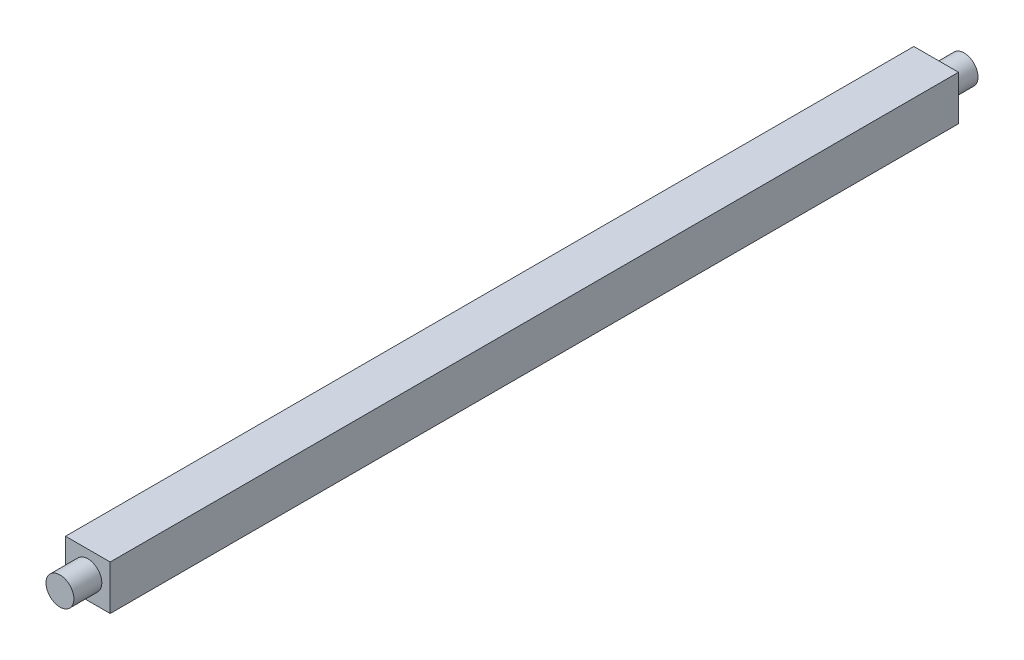
SolidWorks part; units mm, degrees
ref_plane "Alzado" through (0, 0, 0) normal (0, 0, 1) x (1, 0, 0)
ref_plane "Planta" through (0, 0, 0) normal (0, 1, 0) x (1, 0, 0)
ref_plane "Vista lateral" through (0, 0, 0) normal (1, 0, 0) x (0, 0, -1)
sketch "Croquis1" plane through (0, 0, 0) normal (0, 0, 1) x (1, 0, 0)
  line L1 (-4, -4) -> (4, -4)
  line L2 (-4, -4) -> (-4, 4)
  line L3 (-4, 4) -> (4, 4)
  line L4 (4, -4) -> (4, 4)
  line L5 (-4, -4) -> (4, 4) construction
  line L6 (-4, 4) -> (4, -4) construction
  point P0 (0, 0)
  dimension "D1" = 8
  dimension "D2" = 8
extrude "Saliente-Extruir1" add sketch "Croquis1" along normal mid plane 152
sketch "Croquis2" plane through (0, 0, 76) normal (0, 0, 1) x (1, 0, 0)
  circle A0 centre (0, 0) radius 2.5
  dimension "D1" = 5
extrude "Saliente-Extruir2" add sketch "Croquis2" along normal blind 5
sketch "Croquis3" plane through (0, 0, -76) normal (0, 0, -1) x (-1, 0, 0)
  circle A0 centre (0, 0) radius 2.5
  dimension "D1" = 5
extrude "Saliente-Extruir3" add sketch "Croquis3" along normal blind 5
